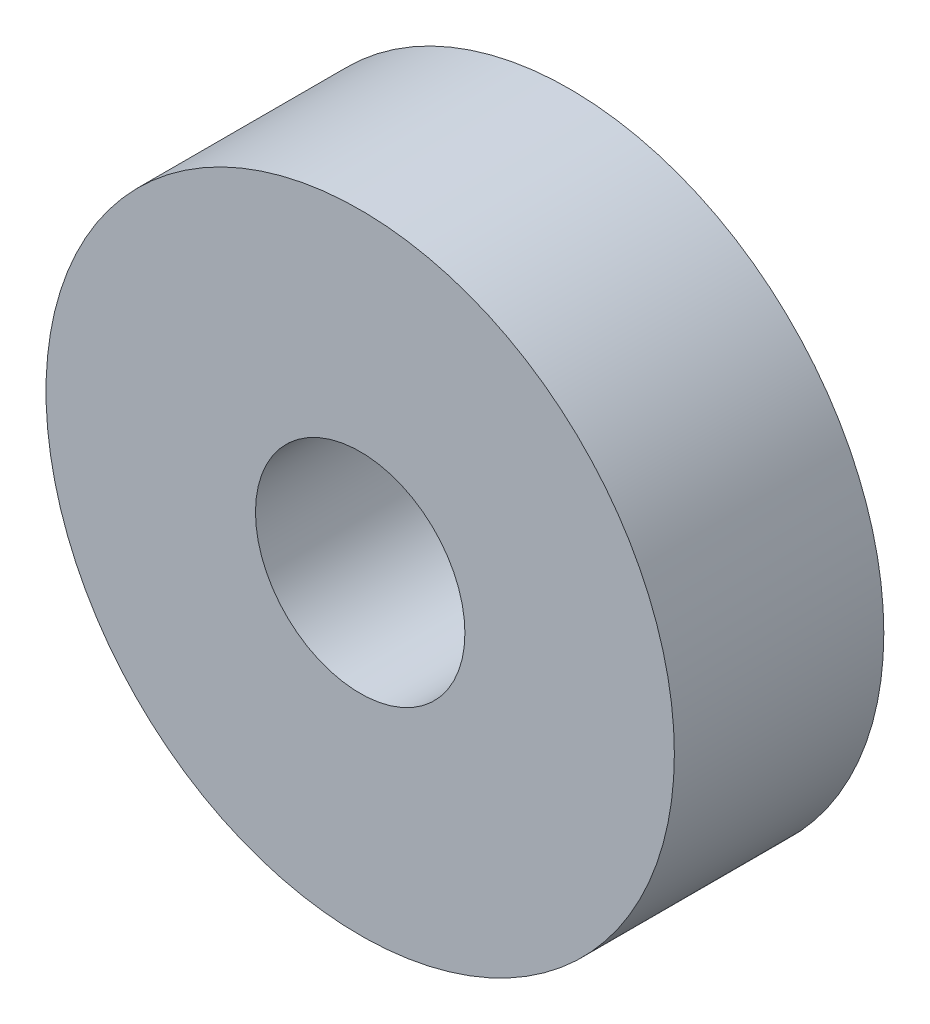
SolidWorks part; units mm, degrees
ref_plane "Alzado" through (0, 0, 0) normal (0, 0, 1) x (1, 0, 0)
ref_plane "Planta" through (0, 0, 0) normal (0, 1, 0) x (1, 0, 0)
ref_plane "Vista lateral" through (0, 0, 0) normal (1, 0, 0) x (0, 0, -1)
sketch "Croquis1" plane through (0, 0, 0) normal (0, 0, 1) x (1, 0, 0)
  circle A0 centre (0, 0) radius 12
  circle A1 centre (0, 0) radius 4
  dimension "D1" = 24
  dimension "D2" = 8
extrude "Saliente-Extruir1" add sketch "Croquis1" along normal blind 8
